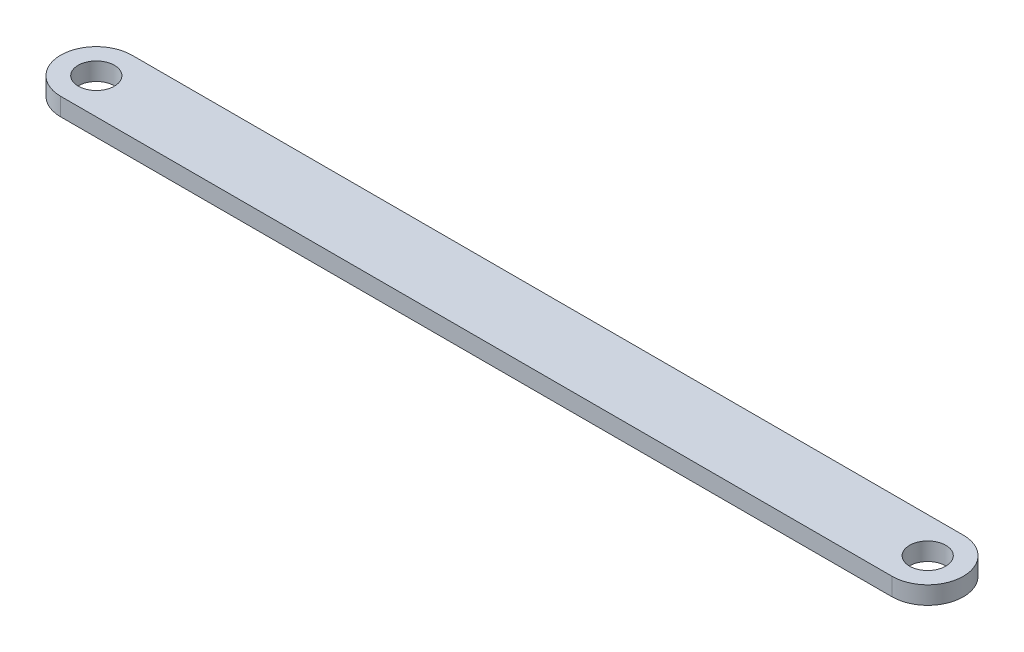
SolidWorks part; units mm, degrees
material "ABS"
ref_plane "Front Plane" through (0, 0, 0) normal (0, 0, 1) x (1, 0, 0)
ref_plane "Top Plane" through (0, 0, 0) normal (0, 1, 0) x (1, 0, 0)
ref_plane "Right Plane" through (0, 0, 0) normal (1, 0, 0) x (0, 0, -1)
sketch "Sketch1" plane through (0, 0, 0) normal (0, 1, 0) x (1, 0, 0)
  line L0 (0, 0) -> (140, 0) construction
  line L1 (0, 6) -> (140, 6)
  line L2 (0, -6) -> (140, -6)
  arc A0 (0, 6) -> (0, -6) centre (0, 0) ccw
  arc A1 (140, -6) -> (140, 6) centre (140, 0) ccw
  circle A2 centre (0, 0) radius 3.05
  circle A3 centre (140, 0) radius 3.05
  point P3 (70, 0)
  dimension "D3" = 6.1
  dimension "D1" = 140
  dimension "D2" = 12
extrude "Boss-Extrude1" add sketch "Sketch1" along normal blind 3
